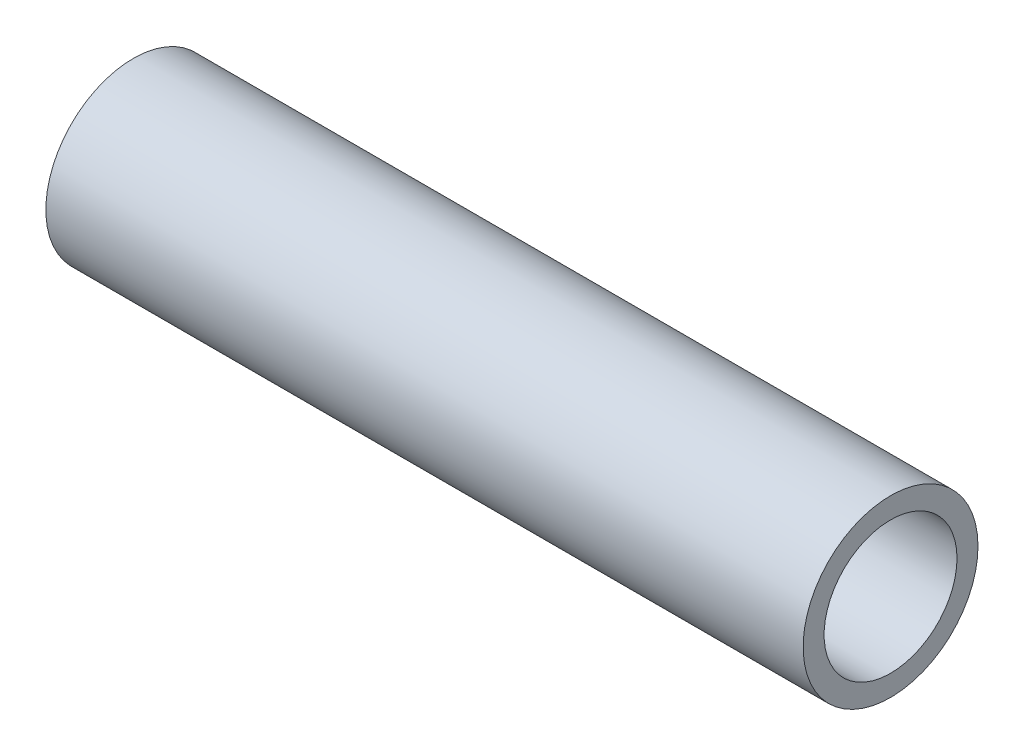
SolidWorks part; units mm, degrees
material "AISI 4130 Steel, annealed at 865C"
ref_plane "Front Plane" through (0, 0, 0) normal (0, 0, 1) x (1, 0, 0)
ref_plane "Top Plane" through (0, 0, 0) normal (0, 1, 0) x (1, 0, 0)
ref_plane "Right Plane" through (0, 0, 0) normal (1, 0, 0) x (0, 0, -1)
sketch "Sketch1" plane through (0, 0, 0) normal (1, 0, 0) x (0, 0, -1)
  circle A0 centre (0, 0) radius 12.7
  circle A1 centre (0, 0) radius 9.652
  dimension "D1" = 25.4
  dimension "D2" = 19.304
extrude "Boss-Extrude1" add sketch "Sketch1" along normal blind 110
